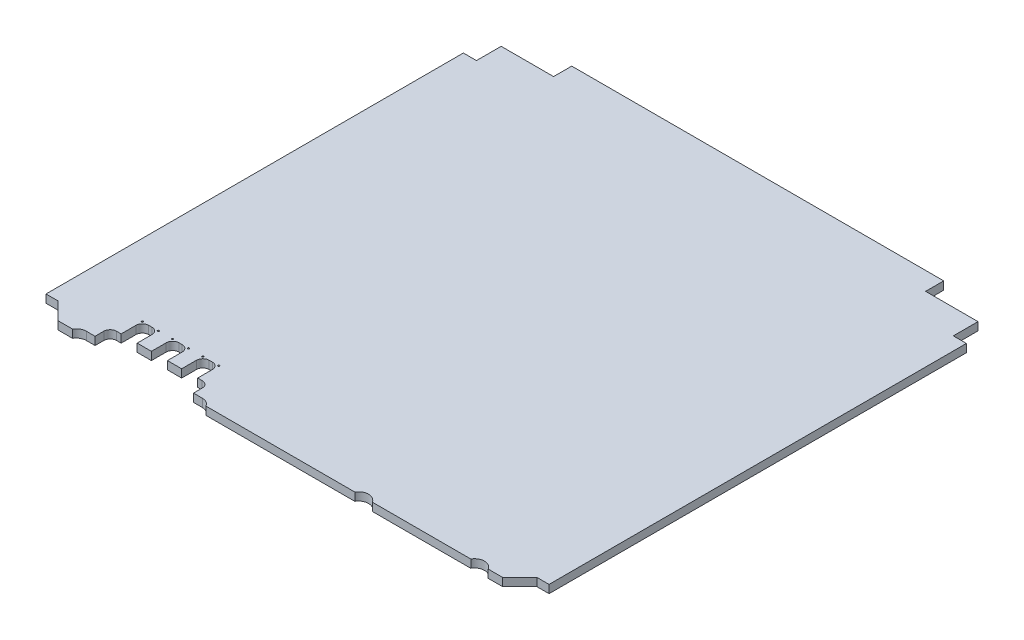
SolidWorks part; units mm, degrees
ref_plane "Front Plane" through (0, 0, 0) normal (0, 0, 1) x (1, 0, 0)
ref_plane "Top Plane" through (0, 0, 0) normal (0, 1, 0) x (1, 0, 0)
ref_plane "Right Plane" through (0, 0, 0) normal (1, 0, 0) x (0, 0, -1)
sketch "Sketch2" plane through (0, 0, 0) normal (0, 1, 0) x (1, 0, 0)
  line L0 (41.5, -47.4) -> (47.4, -41.5)
  line L1 (47.4, -41.5) -> (50, -41.5)
  line L2 (50, -41.5) -> (50, 41.5)
  line L3 (50, 41.5) -> (47.4, 41.5)
  line L4 (47.4, 41.5) -> (47.4, 46.4)
  line L8 (37, 46.4) -> (37, 50)
  line L9 (37, 50) -> (-37, 50)
  line L10 (-37, 50) -> (-37, 46.4)
  line L14 (-47.4, 46.4) -> (-47.4, 41.5)
  line L15 (-47.4, 41.5) -> (-50, 41.5)
  line L16 (-50, 41.5) -> (-50, -41.5)
  line L17 (-50, -41.5) -> (-47.4, -41.5)
  line L18 (-47.4, -41.5) -> (-41.5, -47.4)
  line L19 (-41.5, -47.4) -> (41.5, -47.4)
  line L20 (47.4, 46.4) -> (37, 46.4)
  line L21 (-47.4, 46.4) -> (-37, 46.4)
  line L22 (47.4, -41.5) -> (47.4, 41.5)
  line L23 (-47.4, 41.5) -> (-47.4, -41.5)
  line L24 (37, 46.4) -> (-37, 46.4)
  line L25 (-41.5, 46.4) -> (-41.5, -47.4)
  line L27 (41.5, 46.4) -> (41.5, -47.4)
extrude "GeneralShape" add sketch "Sketch2" along normal mid plane 1.6
sketch "Sketch3" plane through (0, 0, 0) normal (0, 1, 0) x (1, 0, 0)
  line L8 (-47.3, 46.3) -> (-47.3, 41.4)
  line L9 (-47.3, 46.3) -> (-47.3, 41.4)
  line L10 (-47.3, 41.4) -> (-49.9, 41.4)
  line L11 (-47.3, 41.4) -> (-49.9, 41.4)
  line L12 (-47.4, 46.4) -> (-47.4, 41.5)
  line L14 (-47.4, 46.4) -> (-47.4, 41.5)
  line L24 (-47.4, -41.5) -> (-47.5, -41.4)
  line L25 (47.4, -41.5) -> (47.5, -41.4)
  line L31 (-49.9, 41.4) -> (-49.9, -41.4)
  line L48 (-49.9, 41.4) -> (-49.9, -41.4)
  line L49 (-36.9, 46.3) -> (-47.3, 46.3)
  line L50 (-49.9, -41.4) -> (-47.3586, -41.4)
  line L51 (-49.9, -41.4) -> (-47.5, -41.4)
  line L52 (-47.3586, -41.4) -> (-41.4586, -47.3)
  line L53 (41.4586, -47.3) -> (47.3586, -41.4)
  line L54 (47.3586, -41.4) -> (49.9, -41.4)
  line L55 (-41.4586, -47.3) -> (41.4586, -47.3)
  line L56 (47.5, -41.4) -> (49.9, -41.4)
  line L57 (49.9, -41.4) -> (49.9, 41.4)
  line L58 (49.9, -41.4) -> (49.9, 41.4)
  line L59 (49.9, 41.4) -> (47.3, 41.4)
  line L61 (49.9, 41.4) -> (47.3, 41.4)
  line L62 (47.3, 46.3) -> (36.9, 46.3)
  line L63 (47.3, 46.3) -> (36.9, 46.3)
  line L64 (36.9, 46.3) -> (36.9, 49.9)
  line L65 (36.9, 46.3) -> (36.9, 49.9)
  line L66 (-36.9, 46.3) -> (-47.3, 46.3)
  line L82 (47.3, 41.4) -> (47.3, 46.3)
  line L83 (47.3, 41.4) -> (47.3, 46.3)
  line L84 (-47.4, 41.5) -> (-50, 41.5)
  line L85 (-47.4, 41.5) -> (-50, 41.5)
  line L86 (-50, 41.5) -> (-50, -41.5)
  line L87 (-50, 41.5) -> (-50, -41.5)
  line L88 (-50, -41.5) -> (-47.4, -41.5)
  line L89 (-37, 46.4) -> (-47.4, 46.4)
  line L90 (-50, -41.5) -> (-47.4, -41.5)
  line L91 (-47.4, -41.5) -> (-41.5, -47.4)
  line L92 (-47.4, -41.5) -> (-41.5, -47.4)
  line L93 (41.5, -47.4) -> (47.4, -41.5)
  line L94 (41.5, -47.4) -> (47.4, -41.5)
  line L95 (-41.5, -47.4) -> (41.5, -47.4)
  line L96 (47.4, -41.5) -> (50, -41.5)
  line L97 (47.4, -41.5) -> (50, -41.5)
  line L98 (50, -41.5) -> (50, 41.5)
  line L99 (50, -41.5) -> (50, 41.5)
  line L100 (50, 41.5) -> (47.4, 41.5)
  line L101 (36.9, 49.9) -> (-36.9, 49.9)
  line L102 (36.9, 49.9) -> (-36.9, 49.9)
  line L103 (-36.9, 49.9) -> (-36.9, 46.3)
  line L104 (-36.9, 49.9) -> (-36.9, 46.3)
  line L105 (-37, 46.4) -> (-47.4, 46.4)
  line L111 (-41.5, -47.4) -> (41.5, -47.4)
  line L121 (50, 41.5) -> (47.4, 41.5)
  line L122 (47.4, 41.5) -> (47.4, 46.4)
  line L123 (47.4, 41.5) -> (47.4, 46.4)
  line L124 (47.4, 46.4) -> (37, 46.4)
  line L125 (47.4, 46.4) -> (37, 46.4)
  line L126 (37, 46.4) -> (37, 50)
  line L127 (37, 46.4) -> (37, 50)
  line L128 (37, 50) -> (-37, 50)
  line L129 (37, 50) -> (-37, 50)
  line L130 (-37, 50) -> (-37, 46.4)
  line L131 (-37, 50) -> (-37, 46.4)
  dimension "D2" = 0
  dimension "D1" = 0.1
extrude "AddTolerance" cut sketch "Sketch3" against normal through all both and the other way through all contours L129 L131 L105 L14 L85 L87 L90 L24 L51 L48 L11 L9 L66 L104 L102 L65 L63 L83 L61 L58 L56 L25 L97 L99 L121 L123 L125 L127
sketch "Sketch4" plane through (0, 0, 0) normal (0, 1, 0) x (1, 0, 0)
  line L0 (41.5, -47.4) -> (47.5, -41.4) construction
  line L1 (-41.5, -47.4) -> (41.5, -47.4) construction
  line L2 (-47.5, -41.4) -> (-41.5, -47.4) construction
  line L3 (41.5, -47.4) -> (47.5, -41.4)
  line L4 (-41.5, -47.4) -> (41.5, -47.4)
  line L5 (-47.5, -41.4) -> (-41.5, -47.4)
  line L6 (43.1, -45.8) -> (-43.1, -45.8)
  line L7 (39.5, -58.0217) -> (39.5, -38.2748) construction
  line L8 (0, -103.1759) -> (0, 74.8228) construction
  line L9 (-44.1, -44.8) -> (44.1, -44.8)
  line L10 (16.5, -38.2748) -> (16.5, -56.9566) construction
  line L12 (-16.5, -57.9566) -> (-16.5, -39.2748) construction
  line L14 (-39.5, -38.2748) -> (-39.5, -56.9566) construction
  circle A0 centre (39.5, -45.8) radius 2
  circle A1 centre (16.5, -45.8) radius 2
  circle A2 centre (-16.5, -45.8) radius 2
  circle A3 centre (-39.5, -45.8) radius 2
  dimension "D3" = 4
  dimension "D1" = 1.6
  dimension "D2" = 1
  dimension "D4" = 39.5
  dimension "D5" = 16.5
extrude "Backplane" cut sketch "Sketch4" against normal through all both and the other way through all contours L3 L6 L5 L4 | L9 L5 L6 L3 | A1 L6 A0 L9 | A1 L9 | L9 A1 | L9 A0 | A0 L9 | A0 L6 L3 L9 | A3 L9 L5 L6 | A3 L9 | L9 A3 | A3 L6 A2 L9 | A2 L9 | L9 A2 | L6 A0 | L6 A1 | L6 A2 | L6 A3 | A1 L4 A0 L6 | A0 L4 L3 L6 | A3 L4 A2 L6 | A3 L6 L5 L4
sketch "BuildLimits" plane through (0, 0.8, 0) normal (0, 1, 0) x (1, 0, 0)
  line L0 (41.5, 46.4) -> (41.5, -47.4) construction
  line L1 (-41.5, 46.4) -> (-41.5, -47.4) construction
  line L7 (37, 46.4) -> (-37, 46.4) construction
  line L13 (47.4, -41.5) -> (47.4, 41.5) construction
  line L20 (-47.4, 41.5) -> (-47.4, -41.5) construction
  line L21 (41.5, 46.3) -> (41.5, -44.8)
  line L22 (-41.5, 46.3) -> (-41.5, -44.8)
  line L28 (36.9, 46.4) -> (-36.9, 46.4)
  line L33 (-47.3, 41.4) -> (-49.9, 41.4) construction
  line L34 (47.4, -41.5) -> (47.4, 41.4)
  line L35 (49.9, 41.4) -> (47.3, 41.4) construction
  line L36 (-44.1, -44.8) -> (-41.2321, -44.8) construction
  line L41 (-47.4, 41.5) -> (-47.4, -41.5)
  line L42 (41.2321, -44.8) -> (44.1, -44.8) construction
  line L44 (36.9, 46.3) -> (36.9, 49.9) construction
  line L47 (-36.9, 49.9) -> (-36.9, 46.3) construction
  line L49 (47.3, 46.3) -> (36.9, 46.3) construction
  line L56 (-47.4, 41.4) -> (-47.3, 41.4)
  line L57 (-47.3, 46.3) -> (-47.3, 41.4) construction
  line L60 (-36.9, 46.3) -> (-47.3, 46.3) construction
sketch "RF" plane through (0, 0.8, 0) normal (0, 1, 0) x (1, 0, 0)
  line L0 (-20.41, -36.6) -> (-23.59, -36.6)
  line L1 (-20.41, -36.6) -> (-20.41, -40.8)
  line L2 (-20.41, -40.8) -> (-23.59, -40.8)
  line L3 (-23.59, -36.6) -> (-23.59, -40.8)
  line L4 (-20.41, -36.6) -> (-23.59, -40.8) construction
  line L5 (-20.41, -40.8) -> (-23.59, -36.6) construction
  line L6 (-26.41, -36.6) -> (-29.59, -36.6)
  line L7 (-26.41, -36.6) -> (-26.41, -40.8)
  line L8 (-26.41, -40.8) -> (-29.59, -40.8)
  line L9 (-29.59, -36.6) -> (-29.59, -40.8)
  line L10 (-26.41, -36.6) -> (-29.59, -40.8) construction
  line L11 (-26.41, -40.8) -> (-29.59, -36.6) construction
  line L12 (-32.41, -36.6) -> (-35.59, -36.6)
  line L13 (-32.41, -36.6) -> (-32.41, -40.8)
  line L14 (-32.41, -40.8) -> (-35.59, -40.8)
  line L15 (-35.59, -36.6) -> (-35.59, -40.8)
  line L16 (-32.41, -36.6) -> (-35.59, -40.8) construction
  line L17 (-32.41, -40.8) -> (-35.59, -36.6) construction
  line L18 (-42.9704, -45.8) -> (-12.7091, -45.8) construction
  line L19 (43.1, -45.8) -> (-43.1, -45.8) construction
  line L20 (-28, -48.6997) -> (-28, -34.2877) construction
  line L21 (-16.5, -43.8) -> (-18.2321, -43.8)
  line L22 (-18.2321, -43.8) -> (-18.2321, -40.8)
  line L23 (-18.2321, -40.8) -> (-20.41, -40.8)
  line L24 (-39.5, -43.8) -> (-37.7679, -43.8)
  line L25 (-37.7679, -43.8) -> (-37.7679, -40.8)
  line L26 (-37.7679, -40.8) -> (-35.59, -40.8)
  line L27 (-23.59, -40.8) -> (-26.41, -40.8)
  line L28 (-32.41, -40.8) -> (-29.59, -40.8)
  line L29 (-37.7679, -44.8) -> (-37.7679, -43.8) construction
  line L30 (-18.2321, -43.8) -> (-18.2321, -44.8) construction
  line L31 (-16.5, -43.8) -> (-16.5, -44.8)
  line L32 (-16.5, -44.8) -> (-39.5, -44.8)
  line L33 (-39.5, -44.8) -> (-39.5, -43.8)
  arc A2 (-37.7679, -44.8) -> (-41.2321, -44.8) centre (-39.5, -45.8) ccw construction
  arc A3 (-14.7679, -44.8) -> (-18.2321, -44.8) centre (-16.5, -45.8) ccw construction
  point P4 (-22, -38.7)
  point P12 (-28, -38.7)
  point P17 (-34, -38.7)
  arc M21 (-41.2321, -44.8) -> (-37.7679, -44.8) centre (-39.5, -45.8) cw
  line M22 (-37.7679, -44.8) -> (-18.2321, -44.8)
  arc M23 (-18.2321, -44.8) -> (-14.7679, -44.8) centre (-16.5, -45.8) cw
  dimension "D1" = 3.18
  dimension "D2" = 4.2
  dimension "D3" = 6
  dimension "D4" = 5
  dimension "D5" = 28
extrude "Cut-Extrude1" cut sketch "RF" against normal through all contours L0 L3 L2 L1 | L6 L9 L8 L7 | L12 L15 L14 L13 | L28 L14 L26 L25 L24 L21 L22 L23 L2 L27 L8 M21 M22 M23
fillet "Fillet1" radius 1.27 8 edges at (-23.59, 0, 36.6) (-20.41, 0, 36.6) (-18.2321, 0, 40.8) (-37.7679, 0, 40.8) (-35.59, 0, 36.6) (-32.41, 0, 36.6) (-29.59, 0, 36.6) (-26.41, 0, 36.6)
hole_wizard "Ø0.32 (0.32) Diameter Hole1" positions "Sketch5" profile "Sketch6" hole size "Ø0.32" standard "ANSI Metric" end condition through all
sketch "Sketch5" plane through (0, 0.8, 0) normal (0, 1, 0) x (1, 0, 0)
  line L0 (-20.41, -40.8) -> (-20.41, -35.7027) construction
  line L2 (-23.59, -35.7027) -> (-23.59, -40.8) construction
  line L3 (-26.41, -40.8) -> (-23.59, -40.8) construction
  line L4 (-23.59, -37.87) -> (-23.59, -40.8) construction
  line L6 (-26.41, -40.8) -> (-26.41, -35.7027) construction
  line L8 (-29.59, -35.7027) -> (-29.59, -40.8) construction
  line L9 (-29.59, -37.87) -> (-29.59, -40.8) construction
  line L11 (-32.41, -40.8) -> (-32.41, -35.8656) construction
  line L13 (-35.59, -35.8656) -> (-35.59, -40.8) construction
  line L14 (-35.59, -37.87) -> (-35.59, -40.8) construction
  line L16 (-19.4836, -36.6) -> (-37.2542, -36.6) construction
  line L18 (-27.68, -36.6) -> (-28.32, -36.6) construction
  point P0 (-20.41, -36.6)
  point P2 (-23.59, -36.6)
  point P4 (-26.41, -36.6)
  point P6 (-29.59, -36.6)
  point P8 (-32.41, -36.6)
  point P10 (-35.59, -36.6)
sketch "Sketch6" plane through (-20.41, 0.8, 36.6) normal (1, 0, 0) x (0, 0, 1)
  line L0 (0, 0) -> (0, 1.6)
  line L1 (0, 1.6) -> (0.16, 1.6)
  line L2 (0.16, 1.6) -> (0.16, 0)
  line L5 (0.16, 0) -> (0, 0)
  line L11 (0, -6.35) -> (0, 107.95) construction
  dimension "Thru Hole Dia." = 0.32
  dimension "Thru Hole Depth" = 1.6
sketch "PinLocation" plane through (0, 0.8, 0) normal (0, 1, 0) x (1, 0, 0)
  line L0 (49.9, -38.856) -> (-49.9, -38.856) construction
  line L1 (49.9, -41.4) -> (49.9, 41.4) construction
  line L2 (-49.9, 41.4) -> (-49.9, -41.4) construction
  line L3 (0, 5.2282) -> (0, -57.3717) construction
  line L4 (49.9, -37.332) -> (-49.9, -37.332) construction
  line L5 (40.0271, -38.094) -> (-1.3484, -38.094) construction
  line L6 (28, -48.6679) -> (28, -34.2049) construction
  point P12 (0, -38.094)
  point P16 (28, -38.094)
  dimension "D1" = 37.332
  dimension "D2" = 38.856
  dimension "D3" = 28
